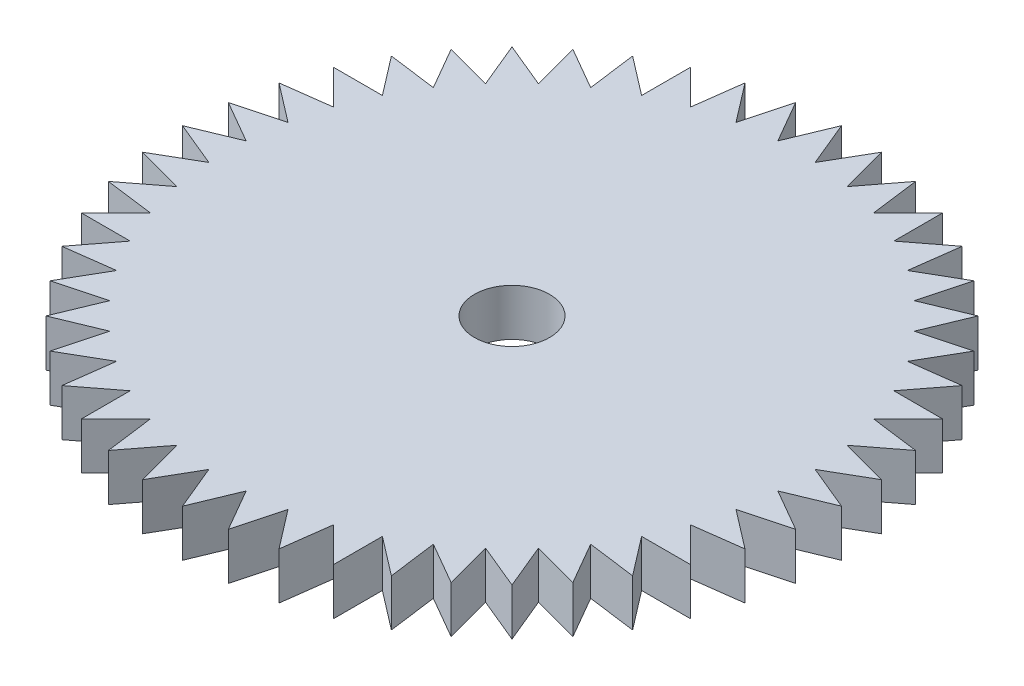
SolidWorks part; units mm, degrees
ref_plane "Front Plane" through (0, 0, 0) normal (0, 0, 1) x (1, 0, 0)
ref_plane "Top Plane" through (0, 0, 0) normal (0, 1, 0) x (1, 0, 0)
ref_plane "Right Plane" through (0, 0, 0) normal (1, 0, 0) x (0, 0, -1)
sketch "Sketch2" plane through (0, 0, 0) normal (0, 1, 0) x (1, 0, 0)
  line L0 (0, 0) -> (34.6259, 17.0756) construction
  line L1 (-17.0756, 34.6259) -> (17.0756, -34.6259) construction
  line L2 (17.0756, -34.6259) -> (12.4099, -36.5585)
  line L3 (12.4099, -36.5585) -> (-12.4099, 36.5585) construction
  line L4 (-12.4099, 36.5585) -> (-14.7428, 35.5922)
  line L5 (-17.0756, 34.6259) -> (-17.0756, 41.2242)
  line L6 (-17.0756, 41.2242) -> (-12.4099, 36.5585)
  line L7 (-17.0756, 41.2242) -> (0, 0) construction
  line L8 (-17.0756, 34.6259) -> (-14.7428, 35.5922)
  line L101 (-12.4099, 36.5585) -> (-9.9709, 37.2121)
  line L102 (-7.5319, 37.8656) -> (-9.9709, 37.2121)
  line L103 (-11.5487, 43.1003) -> (-7.5319, 37.8656)
  line L104 (-12.4099, 36.5585) -> (-11.5487, 43.1003)
  line L105 (-7.5319, 37.8656) -> (-5.0285, 38.1952)
  line L106 (-2.525, 38.5248) -> (-5.0285, 38.1952)
  line L107 (-5.8242, 44.239) -> (-2.525, 38.5248)
  line L108 (-7.5319, 37.8656) -> (-5.8242, 44.239)
  line L109 (-2.525, 38.5248) -> (0, 38.5248)
  line L110 (2.525, 38.5248) -> (0, 38.5248)
  line L111 (0, 44.6208) -> (2.525, 38.5248)
  line L112 (-2.525, 38.5248) -> (0, 44.6208)
  line L113 (2.525, 38.5248) -> (5.0285, 38.1952)
  line L114 (7.5319, 37.8656) -> (5.0285, 38.1952)
  line L115 (5.8242, 44.239) -> (7.5319, 37.8656)
  line L116 (2.525, 38.5248) -> (5.8242, 44.239)
  line L117 (7.5319, 37.8656) -> (9.9709, 37.2121)
  line L118 (12.4099, 36.5585) -> (9.9709, 37.2121)
  line L119 (11.5487, 43.1003) -> (12.4099, 36.5585)
  line L120 (7.5319, 37.8656) -> (11.5487, 43.1003)
  line L121 (12.4099, 36.5585) -> (14.7428, 35.5922)
  line L122 (17.0756, 34.6259) -> (14.7428, 35.5922)
  line L123 (17.0756, 41.2242) -> (17.0756, 34.6259)
  line L124 (12.4099, 36.5585) -> (17.0756, 41.2242)
  line L125 (17.0756, 34.6259) -> (19.2624, 33.3634)
  line L126 (21.4491, 32.1009) -> (19.2624, 33.3634)
  line L127 (22.3104, 38.6427) -> (21.4491, 32.1009)
  line L128 (17.0756, 34.6259) -> (22.3104, 38.6427)
  line L129 (21.4491, 32.1009) -> (23.4524, 30.5637)
  line L130 (25.4556, 29.0266) -> (23.4524, 30.5637)
  line L131 (27.1634, 35.4) -> (25.4556, 29.0266)
  line L132 (21.4491, 32.1009) -> (27.1634, 35.4)
  line L133 (25.4556, 29.0266) -> (27.2411, 27.2411)
  line L134 (29.0266, 25.4556) -> (27.2411, 27.2411)
  line L135 (31.5516, 31.5516) -> (29.0266, 25.4556)
  line L136 (25.4556, 29.0266) -> (31.5516, 31.5516)
  line L137 (29.0266, 25.4556) -> (30.5637, 23.4524)
  line L138 (32.1009, 21.4491) -> (30.5637, 23.4524)
  line L139 (35.4, 27.1634) -> (32.1009, 21.4491)
  line L140 (29.0266, 25.4556) -> (35.4, 27.1634)
  line L141 (32.1009, 21.4491) -> (33.3634, 19.2624)
  line L142 (34.6259, 17.0756) -> (33.3634, 19.2624)
  line L143 (38.6427, 22.3104) -> (34.6259, 17.0756)
  line L144 (32.1009, 21.4491) -> (38.6427, 22.3104)
  line L145 (34.6259, 17.0756) -> (35.5922, 14.7428)
  line L146 (36.5585, 12.4099) -> (35.5922, 14.7428)
  line L147 (41.2242, 17.0756) -> (36.5585, 12.4099)
  line L148 (34.6259, 17.0756) -> (41.2242, 17.0756)
  line L149 (36.5585, 12.4099) -> (37.2121, 9.9709)
  line L150 (37.8656, 7.5319) -> (37.2121, 9.9709)
  line L151 (43.1003, 11.5487) -> (37.8656, 7.5319)
  line L152 (36.5585, 12.4099) -> (43.1003, 11.5487)
  line L153 (37.8656, 7.5319) -> (38.1952, 5.0285)
  line L154 (38.5248, 2.525) -> (38.1952, 5.0285)
  line L155 (44.239, 5.8242) -> (38.5248, 2.525)
  line L156 (37.8656, 7.5319) -> (44.239, 5.8242)
  line L157 (38.5248, 2.525) -> (38.5248, 0)
  line L158 (38.5248, -2.525) -> (38.5248, 0)
  line L159 (44.6208, 0) -> (38.5248, -2.525)
  line L160 (38.5248, 2.525) -> (44.6208, 0)
  line L161 (38.5248, -2.525) -> (38.1952, -5.0285)
  line L162 (37.8656, -7.5319) -> (38.1952, -5.0285)
  line L163 (44.239, -5.8242) -> (37.8656, -7.5319)
  line L164 (38.5248, -2.525) -> (44.239, -5.8242)
  line L165 (37.8656, -7.5319) -> (37.2121, -9.9709)
  line L166 (36.5585, -12.4099) -> (37.2121, -9.9709)
  line L167 (43.1003, -11.5487) -> (36.5585, -12.4099)
  line L168 (37.8656, -7.5319) -> (43.1003, -11.5487)
  line L169 (36.5585, -12.4099) -> (35.5922, -14.7428)
  line L170 (34.6259, -17.0756) -> (35.5922, -14.7428)
  line L171 (41.2242, -17.0756) -> (34.6259, -17.0756)
  line L172 (36.5585, -12.4099) -> (41.2242, -17.0756)
  line L173 (34.6259, -17.0756) -> (33.3634, -19.2624)
  line L174 (32.1009, -21.4491) -> (33.3634, -19.2624)
  line L175 (38.6427, -22.3104) -> (32.1009, -21.4491)
  line L176 (34.6259, -17.0756) -> (38.6427, -22.3104)
  line L177 (32.1009, -21.4491) -> (30.5637, -23.4524)
  line L178 (29.0266, -25.4556) -> (30.5637, -23.4524)
  line L179 (35.4, -27.1634) -> (29.0266, -25.4556)
  line L180 (32.1009, -21.4491) -> (35.4, -27.1634)
  line L181 (29.0266, -25.4556) -> (27.2411, -27.2411)
  line L182 (25.4556, -29.0266) -> (27.2411, -27.2411)
  line L183 (31.5516, -31.5516) -> (25.4556, -29.0266)
  line L184 (29.0266, -25.4556) -> (31.5516, -31.5516)
  line L185 (25.4556, -29.0266) -> (23.4524, -30.5637)
  line L186 (21.4491, -32.1009) -> (23.4524, -30.5637)
  line L187 (27.1634, -35.4) -> (21.4491, -32.1009)
  line L188 (25.4556, -29.0266) -> (27.1634, -35.4)
  line L189 (21.4491, -32.1009) -> (19.2624, -33.3634)
  line L190 (17.0756, -34.6259) -> (19.2624, -33.3634)
  line L191 (22.3104, -38.6427) -> (17.0756, -34.6259)
  line L192 (21.4491, -32.1009) -> (22.3104, -38.6427)
  line L193 (17.0756, -34.6259) -> (14.7428, -35.5922)
  line L194 (12.4099, -36.5585) -> (14.7428, -35.5922)
  line L195 (17.0756, -41.2242) -> (12.4099, -36.5585)
  line L196 (17.0756, -34.6259) -> (17.0756, -41.2242)
  line L197 (12.4099, -36.5585) -> (9.9709, -37.2121)
  line L198 (7.5319, -37.8656) -> (9.9709, -37.2121)
  line L199 (11.5487, -43.1003) -> (7.5319, -37.8656)
  line L200 (12.4099, -36.5585) -> (11.5487, -43.1003)
  line L201 (7.5319, -37.8656) -> (5.0285, -38.1952)
  line L202 (2.525, -38.5248) -> (5.0285, -38.1952)
  line L203 (5.8242, -44.239) -> (2.525, -38.5248)
  line L204 (7.5319, -37.8656) -> (5.8242, -44.239)
  line L205 (2.525, -38.5248) -> (0, -38.5248)
  line L206 (-2.525, -38.5248) -> (0, -38.5248)
  line L207 (0, -44.6208) -> (-2.525, -38.5248)
  line L208 (2.525, -38.5248) -> (0, -44.6208)
  line L209 (-2.525, -38.5248) -> (-5.0285, -38.1952)
  line L210 (-7.5319, -37.8656) -> (-5.0285, -38.1952)
  line L211 (-5.8242, -44.239) -> (-7.5319, -37.8656)
  line L212 (-2.525, -38.5248) -> (-5.8242, -44.239)
  line L213 (-7.5319, -37.8656) -> (-9.9709, -37.2121)
  line L214 (-12.4099, -36.5585) -> (-9.9709, -37.2121)
  line L215 (-11.5487, -43.1003) -> (-12.4099, -36.5585)
  line L216 (-7.5319, -37.8656) -> (-11.5487, -43.1003)
  line L217 (-12.4099, -36.5585) -> (-14.7428, -35.5922)
  line L218 (-17.0756, -34.6259) -> (-14.7428, -35.5922)
  line L219 (-17.0756, -41.2242) -> (-17.0756, -34.6259)
  line L220 (-12.4099, -36.5585) -> (-17.0756, -41.2242)
  line L221 (-17.0756, -34.6259) -> (-19.2624, -33.3634)
  line L222 (-21.4491, -32.1009) -> (-19.2624, -33.3634)
  line L223 (-22.3104, -38.6427) -> (-21.4491, -32.1009)
  line L224 (-17.0756, -34.6259) -> (-22.3104, -38.6427)
  line L225 (-21.4491, -32.1009) -> (-23.4524, -30.5637)
  line L226 (-25.4556, -29.0266) -> (-23.4524, -30.5637)
  line L227 (-27.1634, -35.4) -> (-25.4556, -29.0266)
  line L228 (-21.4491, -32.1009) -> (-27.1634, -35.4)
  line L229 (-25.4556, -29.0266) -> (-27.2411, -27.2411)
  line L230 (-29.0266, -25.4556) -> (-27.2411, -27.2411)
  line L231 (-31.5516, -31.5516) -> (-29.0266, -25.4556)
  line L232 (-25.4556, -29.0266) -> (-31.5516, -31.5516)
  line L233 (-29.0266, -25.4556) -> (-30.5637, -23.4524)
  line L234 (-32.1009, -21.4491) -> (-30.5637, -23.4524)
  line L235 (-35.4, -27.1634) -> (-32.1009, -21.4491)
  line L236 (-29.0266, -25.4556) -> (-35.4, -27.1634)
  line L237 (-32.1009, -21.4491) -> (-33.3634, -19.2624)
  line L238 (-34.6259, -17.0756) -> (-33.3634, -19.2624)
  line L239 (-38.6427, -22.3104) -> (-34.6259, -17.0756)
  line L240 (-32.1009, -21.4491) -> (-38.6427, -22.3104)
  line L241 (-34.6259, -17.0756) -> (-35.5922, -14.7428)
  line L242 (-36.5585, -12.4099) -> (-35.5922, -14.7428)
  line L243 (-41.2242, -17.0756) -> (-36.5585, -12.4099)
  line L244 (-34.6259, -17.0756) -> (-41.2242, -17.0756)
  line L245 (-36.5585, -12.4099) -> (-37.2121, -9.9709)
  line L246 (-37.8656, -7.5319) -> (-37.2121, -9.9709)
  line L247 (-43.1003, -11.5487) -> (-37.8656, -7.5319)
  line L248 (-36.5585, -12.4099) -> (-43.1003, -11.5487)
  line L249 (-37.8656, -7.5319) -> (-38.1952, -5.0285)
  line L250 (-38.5248, -2.525) -> (-38.1952, -5.0285)
  line L251 (-44.239, -5.8242) -> (-38.5248, -2.525)
  line L252 (-37.8656, -7.5319) -> (-44.239, -5.8242)
  line L253 (-38.5248, -2.525) -> (-38.5248, 0)
  line L254 (-38.5248, 2.525) -> (-38.5248, 0)
  line L255 (-44.6208, 0) -> (-38.5248, 2.525)
  line L256 (-38.5248, -2.525) -> (-44.6208, 0)
  line L257 (-38.5248, 2.525) -> (-38.1952, 5.0285)
  line L258 (-37.8656, 7.5319) -> (-38.1952, 5.0285)
  line L259 (-44.239, 5.8242) -> (-37.8656, 7.5319)
  line L260 (-38.5248, 2.525) -> (-44.239, 5.8242)
  line L261 (-37.8656, 7.5319) -> (-37.2121, 9.9709)
  line L262 (-36.5585, 12.4099) -> (-37.2121, 9.9709)
  line L263 (-43.1003, 11.5487) -> (-36.5585, 12.4099)
  line L264 (-37.8656, 7.5319) -> (-43.1003, 11.5487)
  line L265 (-36.5585, 12.4099) -> (-35.5922, 14.7428)
  line L266 (-34.6259, 17.0756) -> (-35.5922, 14.7428)
  line L267 (-41.2242, 17.0756) -> (-34.6259, 17.0756)
  line L268 (-36.5585, 12.4099) -> (-41.2242, 17.0756)
  line L269 (-34.6259, 17.0756) -> (-33.3634, 19.2624)
  line L270 (-32.1009, 21.4491) -> (-33.3634, 19.2624)
  line L271 (-38.6427, 22.3104) -> (-32.1009, 21.4491)
  line L272 (-34.6259, 17.0756) -> (-38.6427, 22.3104)
  line L273 (-32.1009, 21.4491) -> (-30.5637, 23.4524)
  line L274 (-29.0266, 25.4556) -> (-30.5637, 23.4524)
  line L275 (-35.4, 27.1634) -> (-29.0266, 25.4556)
  line L276 (-32.1009, 21.4491) -> (-35.4, 27.1634)
  line L277 (-29.0266, 25.4556) -> (-27.2411, 27.2411)
  line L278 (-25.4556, 29.0266) -> (-27.2411, 27.2411)
  line L279 (-31.5516, 31.5516) -> (-25.4556, 29.0266)
  line L280 (-29.0266, 25.4556) -> (-31.5516, 31.5516)
  line L281 (-25.4556, 29.0266) -> (-23.4524, 30.5637)
  line L282 (-21.4491, 32.1009) -> (-23.4524, 30.5637)
  line L283 (-27.1634, 35.4) -> (-21.4491, 32.1009)
  line L284 (-25.4556, 29.0266) -> (-27.1634, 35.4)
  line L285 (-21.4491, 32.1009) -> (-19.2624, 33.3634)
  line L286 (-17.0756, 34.6259) -> (-19.2624, 33.3634)
  line L287 (-22.3104, 38.6427) -> (-17.0756, 34.6259)
  line L288 (-21.4491, 32.1009) -> (-22.3104, 38.6427)
  circle A0 centre (0, 0) radius 38.6074
  point P6 (-14.7428, 35.5922)
  point P106 (0, 0)
  point P203 (0, 0)
  dimension "D1" = 6.096
  dimension "D2" = 7.5
  dimension "D3" = 48
  dimension "D5" = 45
  dimension "D6" = 77.2148
extrude "Boss-Extrude1" add sketch "Sketch2" along normal blind 6.35 contours A0 L6 L5 | A0 L107 L108 | A0 L111 L112 | A0 L103 L104 | A0 L115 L116 | A0 L119 L120 | A0 L123 L124 | A0 L131 L132 | A0 L135 L136 | A0 L139 L140 | A0 L143 L144 | A0 L147 L148 | A0 L151 L152 | A0 L155 L156 | A0 L159 L160 | A0 L163 L164 | A0 L167 L168 | A0 L171 L172 | A0 L175 L176 | A0 L179 L180 | A0 L183 L184 | A0 L187 L188 | A0 L191 L192 | A0 L287 L288 | A0 L283 L284 | A0 L279 L280 | A0 L127 L128 | A0 L219 L220 | L8 L286 L285 L282 L281 L278 L277 L274 L273 L270 L269 L266 L265 L262 L261 L258 L257 L254 L253 L250 L249 L246 L245 L242 L241 L238 L237 L234 L233 L230 L229 L226 L225 L222 L221 L218 L217 L214 L213 L210 L209 L206 L205 L202 L201 L198 L197 L2 L190 L189 | A0 L207 L208 | A0 L195 L196 | A0 L199 L200 | A0 L203 L204 | A0 L247 L248 | A0 L243 L244 | A0 L239 L240 | A0 L235 L236 | A0 L227 L228 | A0 L231 L232 | A0 L255 L256 | A0 L259 L260 | A0 L263 L264 | A0 L271 L272 | A0 L267 L268 | A0 L275 L276 | A0 L211 L212
sketch "Sketch3" plane through (0, 6.35, 0) normal (0, 1, 0) x (1, 0, 0)
  line L0 (-13.4704, 13.4704) -> (9.525, 16.4978)
  line L1 (9.525, 16.4978) -> (13.4704, -13.4704)
  line L2 (13.4704, -13.4704) -> (-9.525, -16.4978)
  line L3 (-9.525, -16.4978) -> (-13.4704, 13.4704)
  line L4 (-13.4704, 13.4704) -> (13.4704, -13.4704) construction
  line L5 (9.525, 16.4978) -> (-9.525, -16.4978) construction
  line L6 (-11.4977, -1.5137) -> (11.4977, 1.5137) construction
  line L7 (11.4977, 1.5137) -> (1.9727, -14.9841) construction
  line L8 (1.9727, -14.9841) -> (-11.4977, -1.5137) construction
  line L9 (-11.4977, -1.5137) -> (-1.9727, 14.9841) construction
  line L10 (-1.9727, 14.9841) -> (11.4977, 1.5137) construction
  circle A4 centre (0, 0) radius 5.08
  dimension "D1" = 10.16
extrude "Cut-Extrude3" cut sketch "Sketch3" against normal blind 6.35 contours A4
